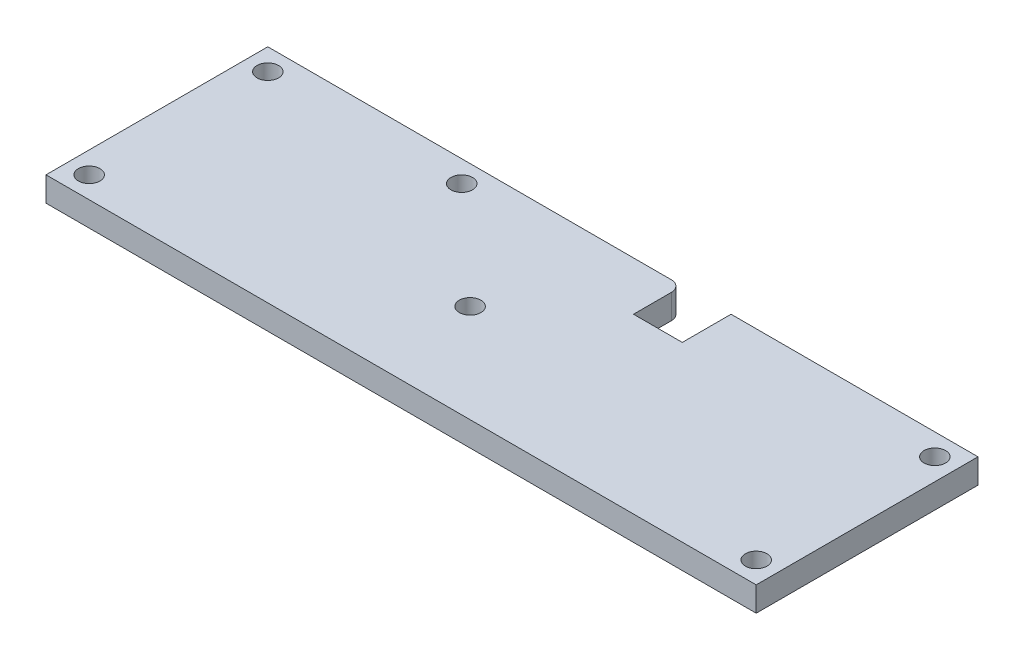
SolidWorks part; units mm, degrees
ref_plane "Front Plane" through (0, 0, 0) normal (0, 0, 1) x (1, 0, 0)
ref_plane "Top Plane" through (0, 0, 0) normal (0, 1, 0) x (1, 0, 0)
ref_plane "Right Plane" through (0, 0, 0) normal (1, 0, 0) x (0, 0, -1)
sketch "Sketch1" plane through (0, 0, 0) normal (0, 1, 0) x (1, 0, 0)
  line L0 (-65, 0) -> (65, 0) construction
  line L1 (65, 20.3) -> (19.8, 20.3)
  line L2 (65, 20.3) -> (65, -20.3)
  line L3 (65, -20.3) -> (-65, -20.3)
  line L4 (-65, 20.3) -> (-65, -20.3)
  line L5 (65, 20.3) -> (-65, -20.3) construction
  line L6 (65, -20.3) -> (-65, 20.3) construction
  line L8 (10.87, 18.3) -> (10.87, 11.37)
  line L9 (10.87, 11.37) -> (19.8, 11.37)
  line L10 (19.8, 20.3) -> (19.8, 11.37)
  line L11 (0, 20.3) -> (0, -20.3) construction
  line L12 (8.87, 20.3) -> (-65, 20.3)
  circle A0 centre (-61.05, 16.35) radius 1.975
  circle A1 centre (61.05, 16.35) radius 1.975
  circle A2 centre (61.05, -16.35) radius 1.975
  circle A3 centre (-61.05, -16.35) radius 1.975
  circle A4 centre (-25.55, 16.35) radius 1.975
  arc A5 (10.87, 18.3) -> (8.87, 20.3) centre (8.87, 18.3) ccw
  circle A6 centre (-5.3283, -2.3397) radius 1.975
  point P0 (0, 0)
  point P26 (10.87, 20.3)
  dimension "D6" = 3.95
  dimension "D9" = 3.95
  dimension "D12" = 2
  dimension "D13" = 3.95
  dimension "D1" = 130
  dimension "D2" = 40.6
  dimension "D3" = 8.93
  dimension "D4" = 8.93
  dimension "D5" = 45.2
  dimension "D7" = 3.95
  dimension "D8" = 3.95
  dimension "D10" = 35.5
  dimension "D11" = 3.95
extrude "Boss-Extrude1" add sketch "Sketch1" along normal blind 4.5
